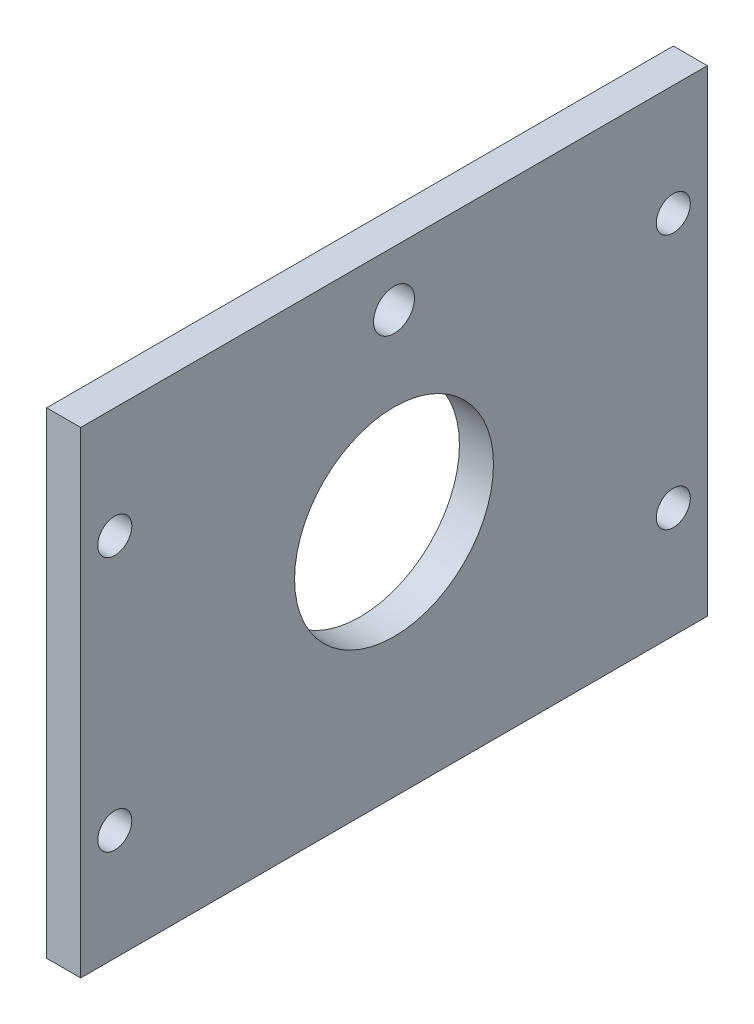
SolidWorks part; units mm, degrees
ref_plane "Front Plane" through (0, 0, 0) normal (0, 0, 1) x (1, 0, 0)
ref_plane "Top Plane" through (0, 0, 0) normal (0, 1, 0) x (1, 0, 0)
ref_plane "Right Plane" through (0, 0, 0) normal (1, 0, 0) x (0, 0, -1)
sketch "Sketch1" plane through (0, 0, 0) normal (1, 0, 0) x (0, 0, -1)
  line L0 (0, 0) -> (92, -70) construction
  line L1 (0, 0) -> (92, 0)
  line L2 (0, 0) -> (0, -70)
  line L3 (0, -70) -> (92, -70)
  line L4 (92, 0) -> (92, -70)
  line L5 (92, 0) -> (0, -70) construction
  line L6 (46, -35) -> (46, 0) construction
  line L7 (46, -17.5) -> (0, -17.5) construction
  circle A0 centre (46, -35) radius 14.6
  dimension "D3" = 29.2
  dimension "D1" = 70
  dimension "D2" = 92
extrude "Boss-Extrude1" add sketch "Sketch1" along normal blind 5
sketch "Sketch2" plane through (5, 0, 0) normal (1, 0, 0) x (0, 0, -1)
  line L0 (0, 0) -> (92, -70) construction
  line L1 (92, -70) -> (92, 0) construction
  line L2 (92, 0) -> (0, -70) construction
  circle A0 centre (5, -53.7276) radius 2.5
  circle A1 centre (5, -16.2724) radius 2.5
  circle A2 centre (87, -53.7276) radius 2.5
  circle A3 centre (87, -16.2724) radius 2.5
extrude "Cut-Extrude1" cut sketch "Sketch2" against normal through all both and the other way through all
sketch "Sketch3" plane through (0, 0, 0) normal (-1, 0, 0) x (0, 0, 1)
  circle A0 centre (-46, -8.0595) radius 3
extrude "Cut-Extrude2" cut sketch "Sketch3" against normal through all both and the other way through all
